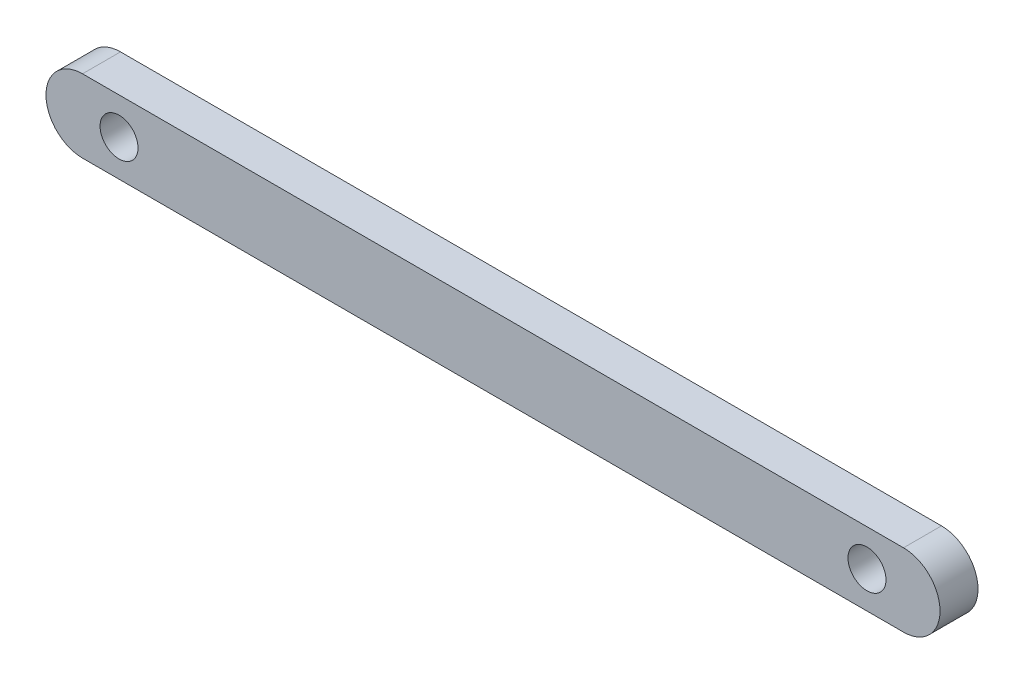
SolidWorks part; units mm, degrees
material "1060 Alloy"
ref_plane "Front" through (0, 0, 0) normal (0, 0, 1) x (1, 0, 0)
ref_plane "Top" through (0, 0, 0) normal (0, 1, 0) x (1, 0, 0)
ref_plane "Right" through (0, 0, 0) normal (1, 0, 0) x (0, 0, -1)
sketch "Sketch1" plane through (0, 0, 0) normal (0, 0, 1) x (1, 0, 0)
  line L0 (0, 0) -> (71.374, 0) construction
  line L1 (0, 3.175) -> (71.374, 3.175)
  line L2 (0, -3.175) -> (71.374, -3.175)
  arc A0 (0, 3.175) -> (0, -3.175) centre (0, 0) ccw
  arc A1 (71.374, -3.175) -> (71.374, 3.175) centre (71.374, 0) ccw
  point P3 (35.687, 0)
  point P8 (-3.175, 0)
  point P9 (74.549, 0)
  dimension "D1" = 77.724
  dimension "D2" = 6.35
extrude "Boss-Extrude1" add sketch "Sketch1" along normal blind 3.302
hole_wizard "1/8 (0.13) Diameter Hole1" positions "Sketch2" profile "Sketch3" hole size "1/8" standard "ANSI Inch" end condition through all
sketch "Sketch2" plane through (0, 0, 3.302) normal (0, 0, 1) x (1, 0, 0)
  arc A0 (0, 3.175) -> (0, -3.175) centre (0, 0) ccw construction
  point P0 (3.175, 0)
  point P2 (68.199, 0)
  point P8 (-3.175, 0)
  point P9 (0, 0)
  dimension "D1" = 65.024
  dimension "D2" = 6.35
sketch "Sketch3" plane through (3.175, 0, 3.302) normal (1, 0, 0) x (0, -1, 0)
  line L0 (0, 0) -> (0, 3.302)
  line L1 (0, 3.302) -> (1.651, 3.302)
  line L2 (1.651, 3.302) -> (1.651, 0)
  line L5 (1.651, 0) -> (0, 0)
  line L11 (0, -6.35) -> (0, 107.95) construction
  dimension "Thru Hole Dia." = 3.302
  dimension "Thru Hole Depth" = 3.302
